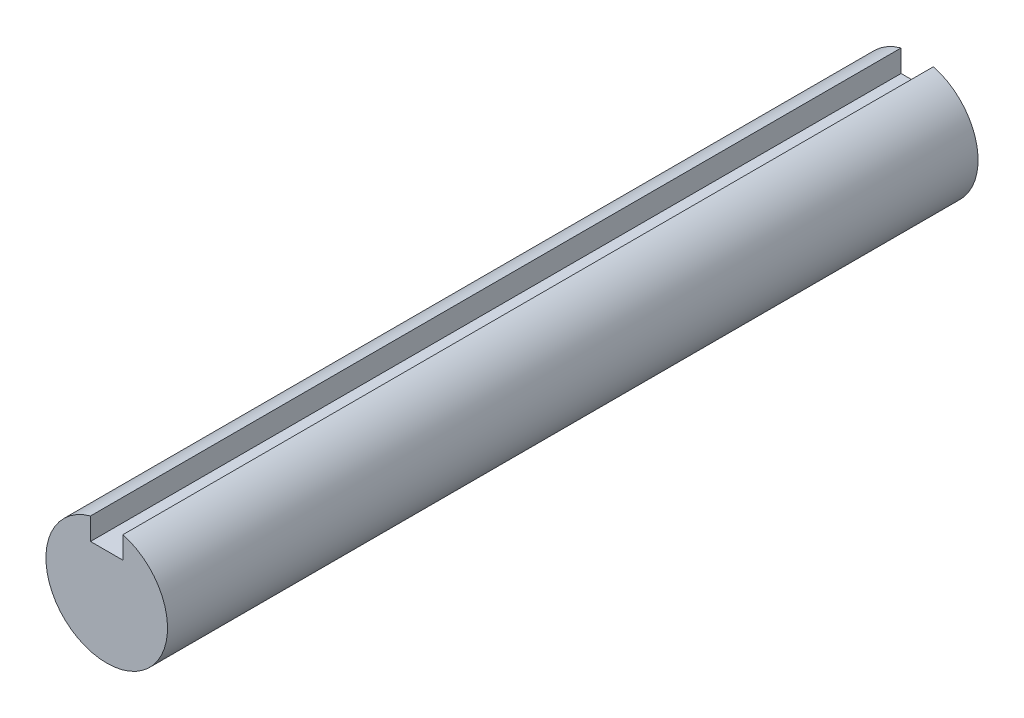
SolidWorks part; units mm, degrees
material "PETG"
ref_plane "Front Plane" through (0, 0, 0) normal (0, 0, 1) x (1, 0, 0)
ref_plane "Top Plane" through (0, 0, 0) normal (0, 1, 0) x (1, 0, 0)
ref_plane "Right Plane" through (0, 0, 0) normal (1, 0, 0) x (0, 0, -1)
sketch "Sketch1" plane through (0, 0, 0) normal (0, 0, 1) x (1, 0, 0)
  circle A0 centre (0, 0) radius 0.75
  dimension "D1" = 1.5
extrude "Boss-Extrude1" add sketch "Sketch1" along normal blind 10
sketch "Sketch3" plane through (0, 0, 10) normal (0, 0, 1) x (1, 0, 0)
  line L1 (0, 0.45) -> (0.2, 0.45)
  line L2 (0, 0.45) -> (0, 0.8075)
  line L3 (0, 0.8075) -> (0.2, 0.8075)
  line L4 (0.2, 0.45) -> (0.2, 0.8075)
  dimension "D1" = 0.45
  dimension "D2" = 0.2
  dimension "D3" = 0.2
extrude "Cut-Extrude1" cut sketch "Sketch3" against normal through all
mirror "Mirror1" about plane through (0, 0, 0) normal (1, 0, 0) of "Cut-Extrude1"
equation "\"rail width\"= 50"
equation "\"system width\"= 125"
equation "\"system depth\"= 250"
equation "\"internal height\"= 100"
equation "\"carriage height\"= 50"
equation "\"gear radius\"= 5"
equation "\"tooth width\"= 1"
equation "\"track width\"= 10"
equation "\"D1@Boss-Extrude1\"= \"track width\""
